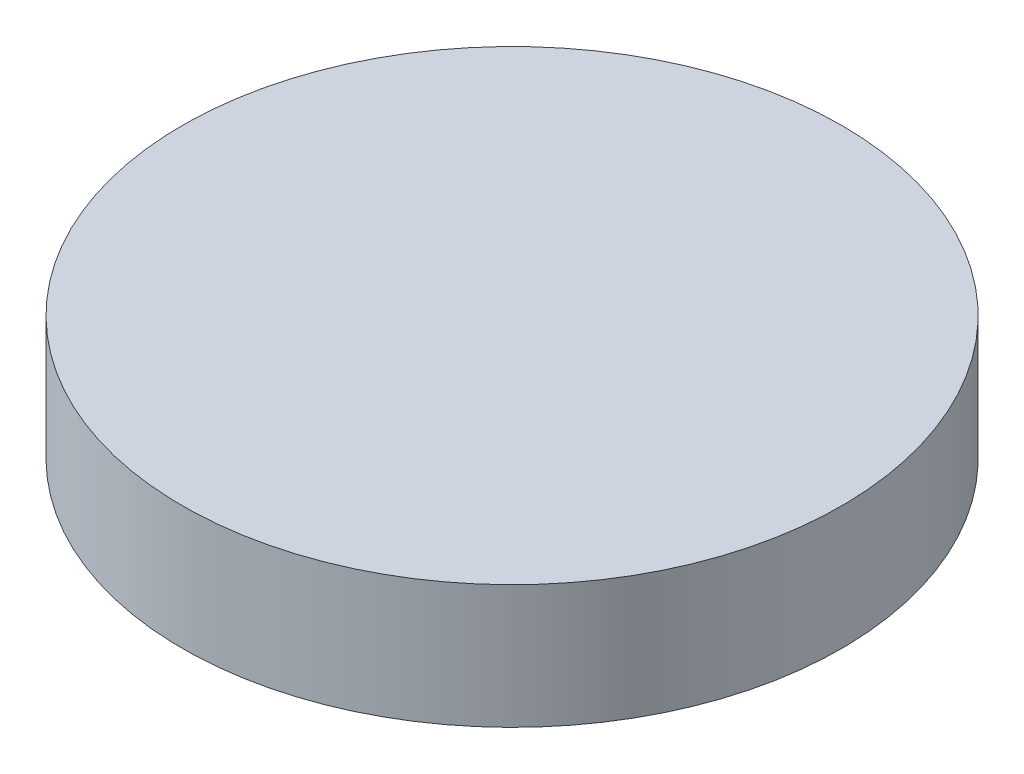
SolidWorks part; units mm, degrees
ref_plane "Front" through (0, 0, 0) normal (0, 0, 1) x (1, 0, 0)
ref_plane "Top" through (0, 0, 0) normal (0, 1, 0) x (1, 0, 0)
ref_plane "Right" through (0, 0, 0) normal (1, 0, 0) x (0, 0, -1)
sketch "Sketch1" plane through (0, 0, 0) normal (0, 1, 0) x (1, 0, 0)
  circle A0 centre (0, 0) radius 50.8
  dimension "D1" = 101.6
extrude "Boss-Extrude1" add sketch "Sketch1" along normal blind 19.05
